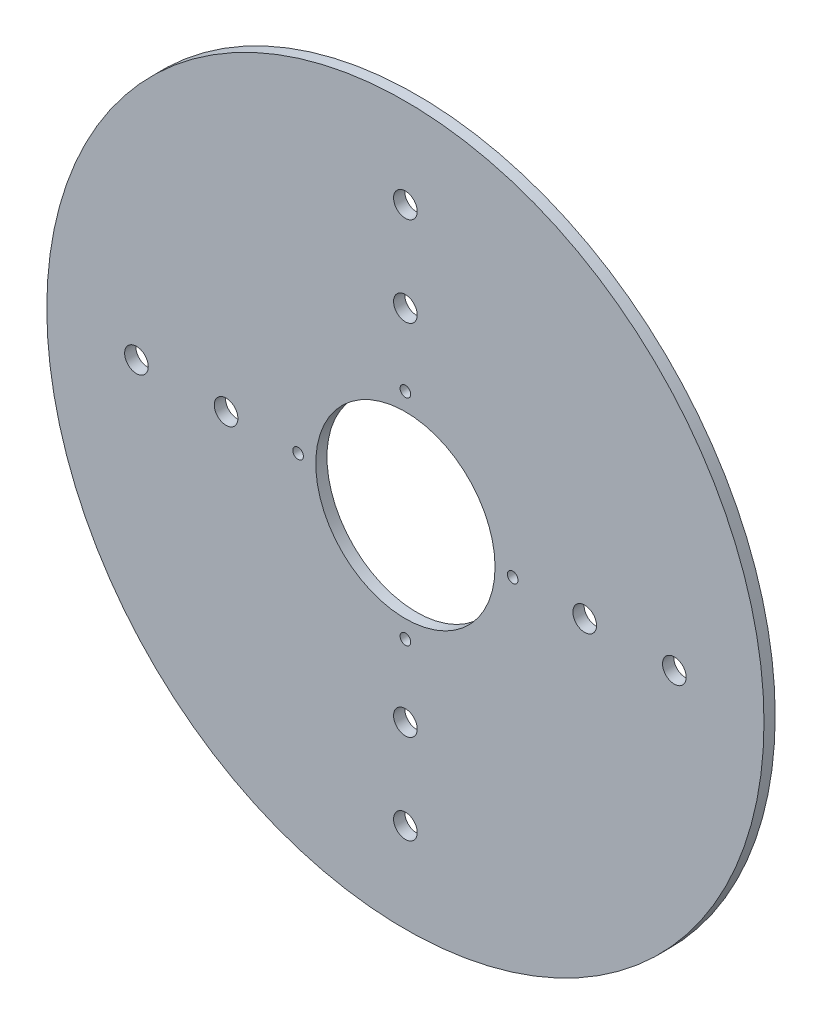
SolidWorks part; units mm, degrees
ref_plane "Front Plane" through (0, 0, 0) normal (0, 0, 1) x (1, 0, 0)
ref_plane "Top Plane" through (0, 0, 0) normal (0, 1, 0) x (1, 0, 0)
ref_plane "Right Plane" through (0, 0, 0) normal (1, 0, 0) x (0, 0, -1)
sketch "Sketch1" plane through (0, 0, 0) normal (0, 0, 1) x (1, 0, 0)
  circle A0 centre (0, 0) radius 101.6
  dimension "D1" = 203.2
extrude "Boss-Extrude1" add sketch "Sketch1" along normal blind 3.175
sketch "Sketch2" plane through (0, 0, 3.175) normal (0, 0, 1) x (1, 0, 0)
  circle A0 centre (0, 0) radius 25.4
  dimension "D1" = 50.8
extrude "Cut-Extrude1" cut sketch "Sketch2" against normal blind 3.175
sketch "Sketch4" plane through (0, 0, 0) normal (0, 0, -1) x (-1, 0, 0)
  circle A0 centre (0, 30.4) radius 1.5
  circle A1 centre (30.4, 0) radius 1.5
  circle A2 centre (0, -30.4) radius 1.5
  circle A3 centre (-30.4, 0) radius 1.5
  circle A4 centre (0, 0) radius 25.4 construction
  dimension "D1" = 3
  dimension "D2" = 3
  dimension "D3" = 3
  dimension "D4" = 3
  dimension "D5" = 30.4
  dimension "D6" = 30.4
  dimension "D7" = 30.4
  dimension "D8" = 30.4
extrude "Cut-Extrude3" cut sketch "Sketch4" against normal blind 10
sketch "Sketch5" plane through (0, 0, 0) normal (0, 0, -1) x (-1, 0, 0)
  circle A0 centre (0, 0) radius 50.8
  circle A1 centre (0, 50.8) radius 3.35
  circle A2 centre (50.8, 0) radius 3.35
  circle A3 centre (0, -50.8) radius 3.35
  circle A4 centre (-50.8, 0) radius 3.35
  dimension "D1" = 6.7
  dimension "D2" = 6.7
  dimension "D3" = 6.7
  dimension "D4" = 6.7
  dimension "D5" = 101.6
extrude "Cut-Extrude4" cut sketch "Sketch5" against normal blind 10 contours A1 | A4 | A3 | A2
sketch "Sketch6" plane through (0, 0, 0) normal (0, 0, -1) x (-1, 0, 0)
  circle A0 centre (0, 0) radius 76.2
  circle A1 centre (-76.2, 0) radius 3.35
  circle A2 centre (0, 76.2) radius 3.35
  circle A3 centre (0, -76.2) radius 3.35
  circle A4 centre (76.2, 0) radius 3.35
  dimension "D1" = 6.7
  dimension "D2" = 6.7
  dimension "D3" = 6.7
  dimension "D4" = 6.7
extrude "Cut-Extrude5" cut sketch "Sketch6" against normal blind 10 contours A1 | A2 | A4 | A3
